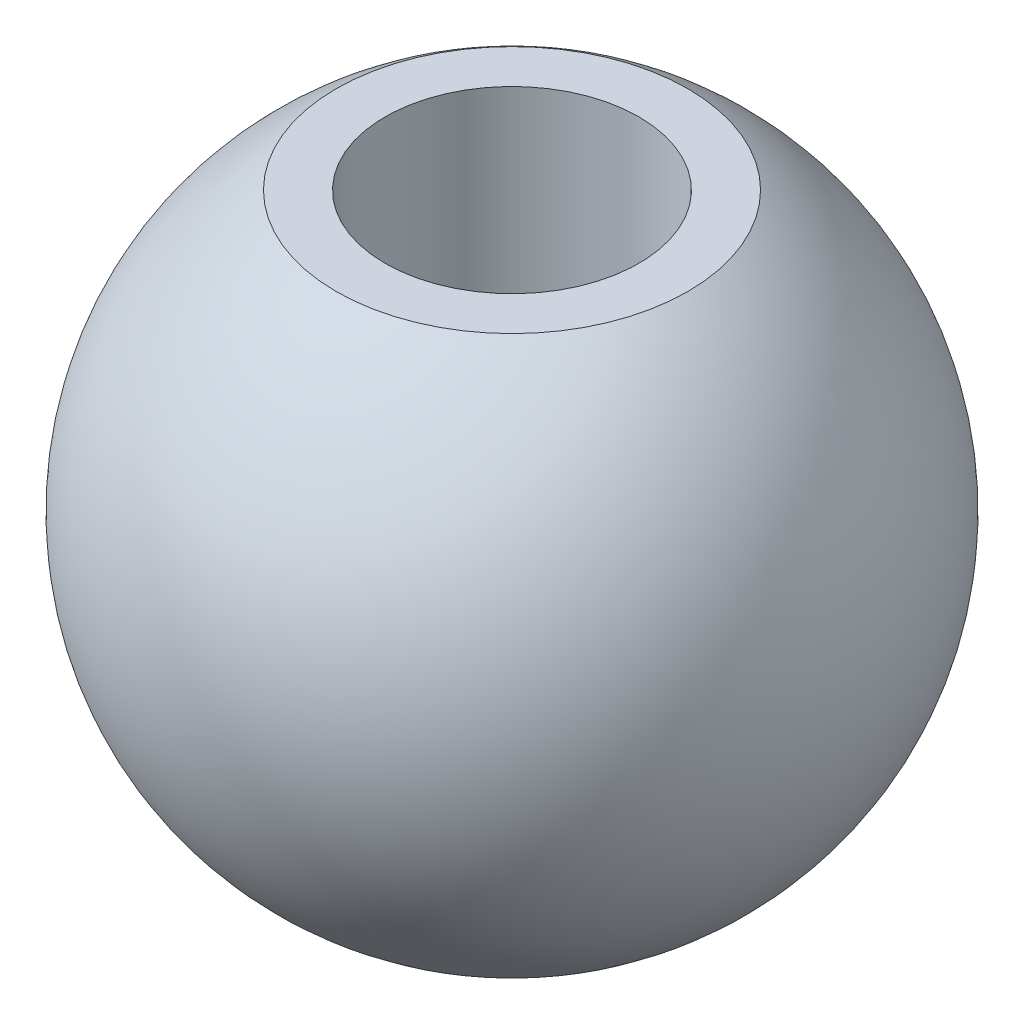
SolidWorks part; units mm, degrees
material "Plain Carbon Steel"
ref_plane "Front Plane" through (0, 0, 0) normal (0, 0, 1) x (1, 0, 0)
ref_plane "Top Plane" through (0, 0, 0) normal (0, 1, 0) x (1, 0, 0)
ref_plane "Right Plane" through (0, 0, 0) normal (1, 0, 0) x (0, 0, -1)
sketch "Sketch1" plane through (0, 0, 0) normal (0, 0, 1) x (1, 0, 0)
  line L0 (0, 74.9387) -> (0, -51.4504) construction
  line L1 (-2.1117, 3.35) -> (-1.525, 3.35)
  line L2 (-1.525, 3.35) -> (-1.525, -3.35)
  line L3 (-1.525, -3.35) -> (-2.1117, -3.35)
  arc A0 (-2.1117, 3.35) -> (-2.1117, -3.35) centre (0, 0) ccw
  dimension "D1" = 3.96
  dimension "D2" = 6.7
  dimension "D3" = 1.525
revolve "Revolve1" add sketch "Sketch1" angle 360 about L0
sketch "Sketch2" plane through (0, 0, 0) normal (0, 1, 0) x (1, 0, 0)
  point P0 (0, 0)
